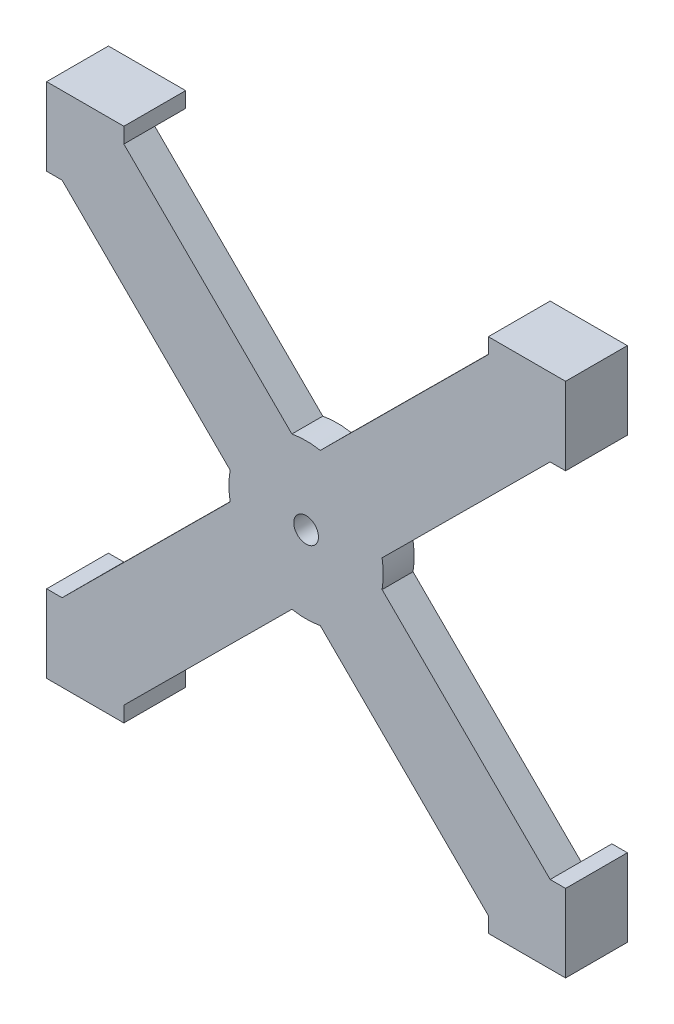
SolidWorks part; units mm, degrees
ref_plane "Alzado" through (0, 0, 0) normal (0, 0, 1) x (1, 0, 0)
ref_plane "Planta" through (0, 0, 0) normal (0, 1, 0) x (1, 0, 0)
ref_plane "Vista lateral" through (0, 0, 0) normal (1, 0, 0) x (0, 0, -1)
sketch "Croquis1" plane through (0, 0, 0) normal (0, 0, 1) x (1, 0, 0)
  line L0 (-59, 78.65) -> (-4.6001, 24.5731)
  line L1 (-79, 78.65) -> (-59, 78.65)
  line L3 (-79, -78.65) -> (-59, -78.65)
  line L5 (-17.7302, 17.6249) -> (17.7302, -17.6249) construction
  line L6 (-79, -78.65) -> (14.6047, 14.54) construction
  line L7 (-79, 58.5305) -> (-24.6001, 4.4537)
  line L8 (0, 78.55) -> (0, 38.8086) construction
  line L9 (79, 58.5305) -> (24.6001, 4.4537)
  line L10 (59, 78.65) -> (4.6001, 24.5731)
  line L11 (78.8, 0) -> (30.3826, 0) construction
  line L12 (-79, -58.5305) -> (-24.6001, -4.4537)
  line L13 (-59, -78.65) -> (-4.6001, -24.5731)
  line L14 (59, -78.65) -> (4.6001, -24.5731)
  line L15 (79, -58.5305) -> (24.6001, -4.4537)
  line L16 (59, 78.65) -> (79, 78.65)
  line L17 (59, -78.65) -> (79, -78.65)
  line L18 (-79, 78.65) -> (-79, 58.5305)
  line L19 (-79, -58.5305) -> (-79, -78.65)
  line L20 (79, -58.5305) -> (79, -78.65)
  line L21 (79, 78.65) -> (79, 58.5305)
  arc A0 (24.6001, -4.4537) -> (24.6001, 4.4537) centre (0, 0) ccw
  circle A1 centre (0, 0) radius 4
  arc A2 (4.6001, 24.5731) -> (-4.6001, 24.5731) centre (0, 0) ccw
  arc A3 (-4.6001, -24.5731) -> (4.6001, -24.5731) centre (0, 0) ccw
  arc A4 (-24.6001, 4.4537) -> (-24.6001, -4.4537) centre (0, 0) ccw
  dimension "D1" = 8
  dimension "D2" = 50
  dimension "D3" = 157.3
  dimension "D4" = 158
  dimension "D5" = 20
  dimension "D6" = 90
  dimension "D7" = 90
extrude "Saliente-Extruir1" add sketch "Croquis1" along normal blind 10
sketch "Croquis4" plane through (0, 0, 10) normal (0, 0, 1) x (1, 0, 0)
  line L1 (-59, 78.65) -> (-79, 78.65)
  line L2 (-59, 78.65) -> (-59, 83.65)
  line L3 (-59, 83.65) -> (-79, 83.65)
  line L5 (0, 25) -> (0, 87.028)
  line L6 (-79, 58.5305) -> (-84, 58.5305)
  line L7 (-79, 58.5305) -> (-79, 78.65)
  line L8 (-79, 83.65) -> (-84, 83.65)
  line L9 (-84, 58.5305) -> (-84, 83.65)
  line L10 (59, 78.65) -> (59, 83.65)
  line L11 (59, 83.65) -> (79, 83.65)
  line L12 (79, 83.65) -> (84, 83.65)
  line L13 (84, 58.5305) -> (84, 83.65)
  line L14 (79, 58.5305) -> (84, 58.5305)
  line L15 (79, 58.5305) -> (79, 78.65)
  line L16 (59, 78.65) -> (79, 78.65)
  line L17 (0, 0) -> (102.2019, 0) construction
  line L18 (59, -78.65) -> (79, -78.65)
  line L19 (79, -58.5305) -> (79, -78.65)
  line L20 (79, -58.5305) -> (84, -58.5305)
  line L21 (84, -58.5305) -> (84, -83.65)
  line L22 (79, -83.65) -> (84, -83.65)
  line L23 (59, -83.65) -> (79, -83.65)
  line L24 (59, -78.65) -> (59, -83.65)
  line L25 (-59, -78.65) -> (-59, -83.65)
  line L26 (-59, -83.65) -> (-79, -83.65)
  line L27 (-79, -83.65) -> (-84, -83.65)
  line L28 (-84, -58.5305) -> (-84, -83.65)
  line L29 (-79, -58.5305) -> (-84, -58.5305)
  line L30 (-79, -58.5305) -> (-79, -78.65)
  line L31 (-59, -78.65) -> (-79, -78.65)
  arc A0 (4.6001, 24.5731) -> (-4.6001, 24.5731) centre (0, 0) ccw construction
  dimension "D1" = 5
  dimension "D2" = 5
extrude "Saliente-Extruir2" add sketch "Croquis4" against normal blind 20 contours L1 L7 L6 L9 L8 L3 L2 | L10 L11 L12 L13 L14 L15 L16 | L25 L26 L27 L28 L29 L30 L31 | L18 L19 L20 L21 L22 L23 L24
